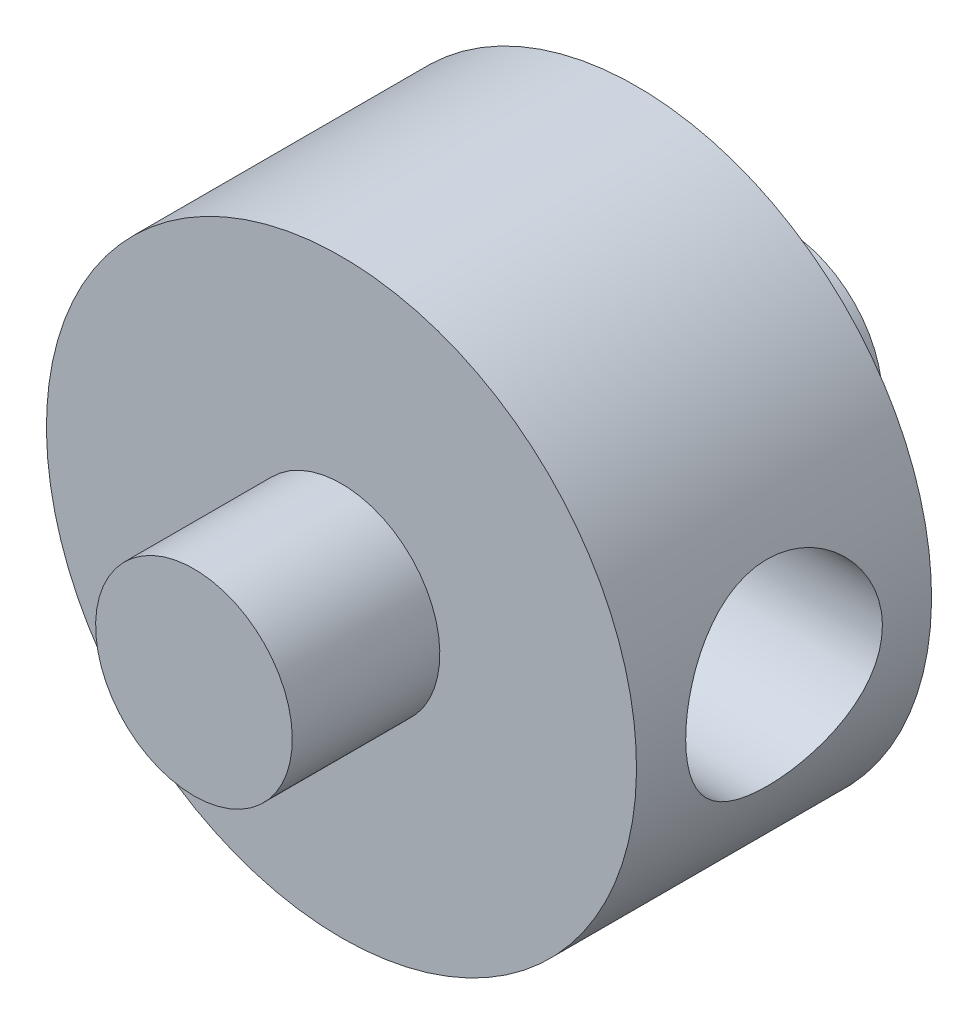
SolidWorks part; units mm, degrees
ref_plane "Front Plane" through (0, 0, 0) normal (0, 0, 1) x (1, 0, 0)
ref_plane "Top Plane" through (0, 0, 0) normal (0, 1, 0) x (1, 0, 0)
ref_plane "Right Plane" through (0, 0, 0) normal (1, 0, 0) x (0, 0, -1)
sketch "Sketch1" plane through (0, 0, 0) normal (1, 0, 0) x (0, 0, -1)
  line L0 (0, 0) -> (19.05, 0)
  line L1 (19.05, 0) -> (19.05, 3.175)
  line L2 (19.05, 3.175) -> (14.2875, 3.175)
  line L3 (14.2875, 3.175) -> (14.2875, 9.525)
  line L4 (14.2875, 9.525) -> (4.7625, 9.525)
  line L5 (4.7625, 9.525) -> (4.7625, 3.175)
  line L6 (4.7625, 3.175) -> (0, 3.175)
  line L7 (0, 3.175) -> (0, 0)
  dimension "D1" = 9.525
  dimension "D2" = 4.7625
  dimension "D3" = 9.525
  dimension "D4" = 3.175
revolve "Revolve1" add sketch "Sketch1" angle 360 about L0
sketch "Sketch2" plane through (0, 0, 0) normal (1, 0, 0) x (0, 0, -1)
  line L0 (4.7625, 9.525) -> (4.7625, -9.525) construction
  circle A0 centre (9.525, 0) radius 3.175
  point P2 (0, 0)
  point P5 (0, 0)
  dimension "D1" = 6.35
  dimension "D2" = 4.7625
extrude "Cut-Extrude1" cut sketch "Sketch2" against normal through all both and the other way through all
